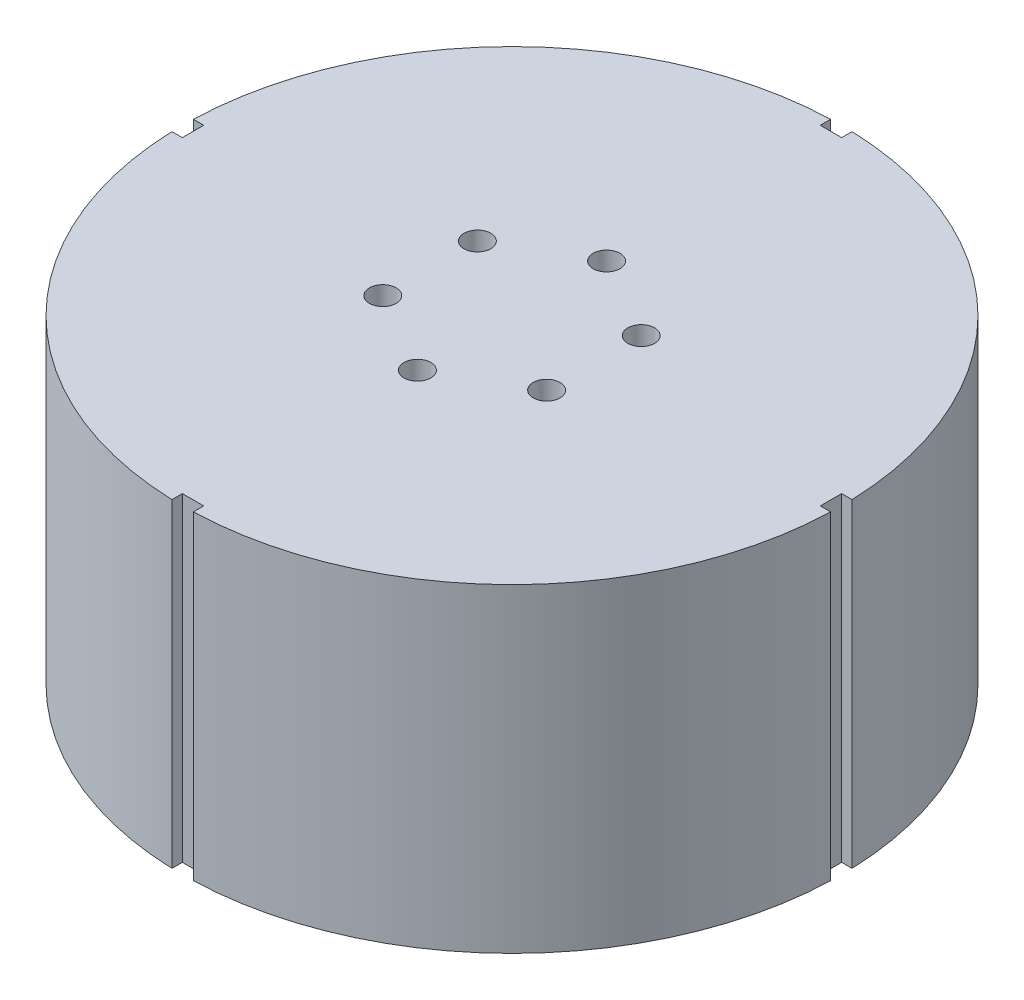
SolidWorks part; units mm, degrees
ref_plane "Front Plane" through (0, 0, 0) normal (0, 0, 1) x (1, 0, 0)
ref_plane "Top Plane" through (0, 0, 0) normal (0, 1, 0) x (1, 0, 0)
ref_plane "Right Plane" through (0, 0, 0) normal (1, 0, 0) x (0, 0, -1)
sketch "Sketch1" plane through (0, 0, 0) normal (0, 1, 0) x (1, 0, 0)
  line L0 (0, 0) -> (0, -54) construction
  line L1 (-1.75, -53.9716) -> (-1.75, -52.2716)
  line L2 (-1.75, -52.2716) -> (1.75, -52.2716)
  line L3 (1.75, -52.2716) -> (1.75, -53.9716)
  line L4 (-52.2716, -1.75) -> (-53.9716, -1.75)
  line L5 (-52.2716, 1.75) -> (-52.2716, -1.75)
  line L6 (-53.9716, 1.75) -> (-52.2716, 1.75)
  line L7 (-1.75, 52.2716) -> (-1.75, 53.9716)
  line L8 (1.75, 52.2716) -> (-1.75, 52.2716)
  line L9 (1.75, 53.9716) -> (1.75, 52.2716)
  line L10 (52.2716, 1.75) -> (53.9716, 1.75)
  line L11 (52.2716, -1.75) -> (52.2716, 1.75)
  line L12 (53.9716, -1.75) -> (52.2716, -1.75)
  circle A0 centre (0, 0) radius 54
  point P6 (0, -52.2716)
  point P24 (0, 0)
  dimension "D1" = 108
  dimension "D2" = 1.7
  dimension "D3" = 3.5
  dimension "D4" = 4
extrude "Boss-Extrude1" add sketch "Sketch1" along normal blind 52.34
sketch "Sketch2" plane through (0, 0, 0) normal (0, -1, 0) x (1, 0, 0)
  circle A0 centre (0, 0) radius 20 construction
  circle A1 centre (0, 0) radius 15.5 construction
  circle A2 centre (0, 15.5) radius 2.2
  circle A3 centre (13.4234, 7.75) radius 2.2
  circle A4 centre (13.4234, -7.75) radius 2.2
  circle A5 centre (0, -15.5) radius 2.2
  circle A6 centre (-13.4234, -7.75) radius 2.2
  circle A7 centre (-13.4234, 7.75) radius 2.2
  point P18 (0, 0)
  dimension "D1" = 40
  dimension "D2" = 31
  dimension "D3" = 4.4
  dimension "D4" = 6
extrude "Cut-Extrude1" cut sketch "Sketch2" against normal blind 80
sketch "Sketch3" plane through (0, 0, 0) normal (0, -1, 0) x (1, 0, 0)
  circle A0 centre (0, 0) radius 49.6
  dimension "D1" = 99.2
extrude "Cut-Extrude2" cut sketch "Sketch3" against normal blind 30
